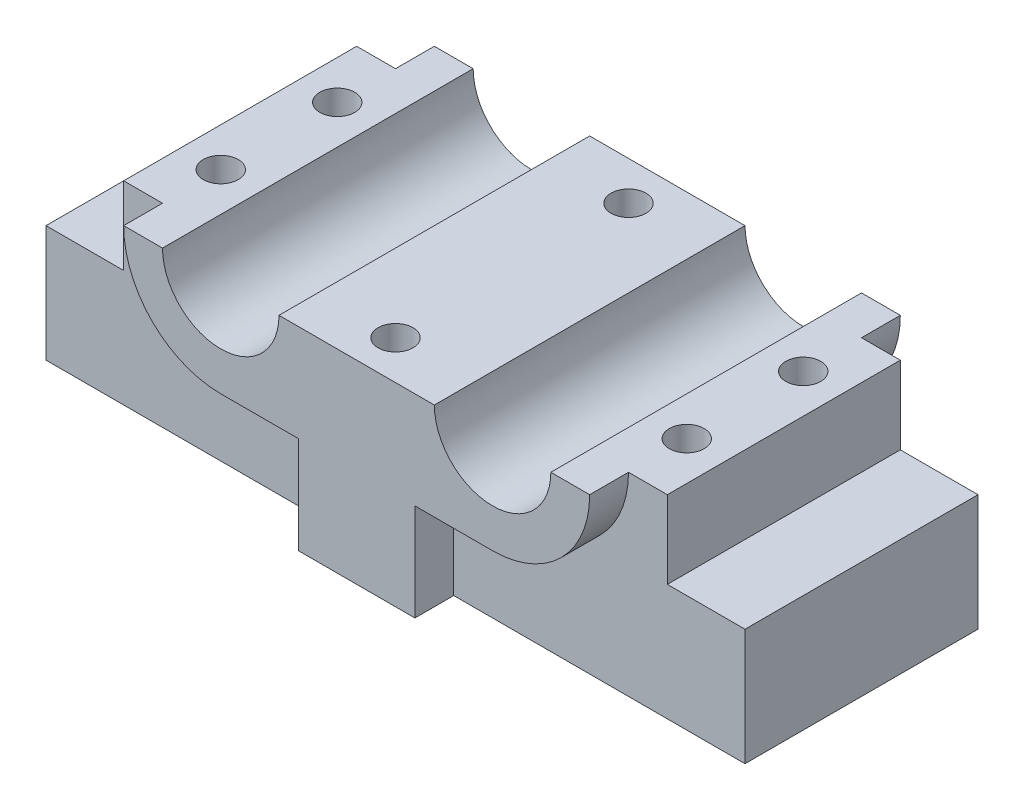
SolidWorks part; units mm, degrees
ref_plane "Front Plane" through (0, 0, 0) normal (0, 0, 1) x (1, 0, 0)
ref_plane "Top Plane" through (0, 0, 0) normal (0, 1, 0) x (1, 0, 0)
ref_plane "Right Plane" through (0, 0, 0) normal (1, 0, 0) x (0, 0, -1)
sketch "Sketch3" plane through (0, 0, 0) normal (0, 0, 1) x (1, 0, 0)
  line L1 (-45, 12.5) -> (45, 12.5)
  line L2 (-45, 12.5) -> (-45, -12.5)
  line L3 (-45, -12.5) -> (45, -12.5)
  line L4 (45, 12.5) -> (45, -12.5)
  line L5 (-45, 12.5) -> (45, -12.5) construction
  line L6 (-45, -12.5) -> (45, 12.5) construction
  point P0 (0, 0)
  dimension "D1" = 90
  dimension "D2" = 25
extrude "Boss-Extrude1" add sketch "Sketch3" along normal mid plane 40
sketch "Sketch4" plane through (0, 0, 20) normal (0, 0, 1) x (1, 0, 0)
  line L1 (-45, 12.5) -> (-35, 12.5)
  line L2 (-45, 12.5) -> (-45, 2.5)
  line L3 (-45, 2.5) -> (-35, 2.5)
  line L4 (-35, 12.5) -> (-35, 2.5)
  line L5 (45, 12.5) -> (35, 12.5)
  line L6 (45, 12.5) -> (45, 2.5)
  line L7 (45, 2.5) -> (35, 2.5)
  line L8 (35, 12.5) -> (35, 2.5)
  point P12 (54.5161, 5.0632)
  dimension "D1" = 10
  dimension "D2" = 10
  dimension "D3" = 10
extrude "Cut-Extrude1" cut sketch "Sketch4" against normal blind 40
sketch "Sketch5" plane through (0, 0, 20) normal (0, 0, 1) x (1, 0, 0)
  line L0 (17.5, 12.5) -> (30, 12.5)
  line L1 (35, 12.5) -> (-35, 12.5) construction
  line L2 (17.5, 0) -> (7.5, 0)
  line L3 (7.5, 0) -> (7.5, -12.5)
  line L4 (-45, -12.5) -> (45, -12.5) construction
  line L5 (7.5, -12.5) -> (45, -12.5)
  line L6 (45, -12.5) -> (45, 2.5)
  line L7 (45, 2.5) -> (35, 2.5)
  line L8 (35, 2.5) -> (35, 12.5)
  line L9 (35, 12.5) -> (30, 12.5)
  line L10 (0, -55) -> (0, 55) construction
  line L11 (-35, 12.5) -> (-30, 12.5)
  line L12 (-35, 2.5) -> (-35, 12.5)
  line L13 (-45, 2.5) -> (-35, 2.5)
  line L14 (-45, -12.5) -> (-45, 2.5)
  line L15 (-7.5, -12.5) -> (-45, -12.5)
  line L16 (-7.5, 0) -> (-7.5, -12.5)
  line L17 (-17.5, 0) -> (-7.5, 0)
  arc A0 (30, 12.5) -> (17.5, 0) centre (17.5, 12.5) cw
  arc A1 (-30, 12.5) -> (-17.5, 0) centre (-17.5, 12.5) ccw
  point P4 (0, 0)
  point P18 (0, 0)
  point P19 (0, 0)
  line M18 (-35, 12.5) -> (-35, 2.5)
  line M19 (-35, 2.5) -> (-45, 2.5)
  line M20 (-45, 2.5) -> (-45, -12.5)
  line M21 (-45, -12.5) -> (45, -12.5)
  line M25 (35, 12.5) -> (-35, 12.5)
  dimension "D2" = 12.5
  dimension "D1" = 17.5
  dimension "D3" = 7.5
extrude "Cut-Extrude2" cut sketch "Sketch5" against normal blind 5 contours A1 L16 L17 M25 M18 M19 M20 M21 | A0 L2 L3 L5 L6 L7 L8 L9
ref_plane "Plane1" through (0, 0, 0) normal (0, 0, -1) x (-1, 0, 0)
mirror "Mirror2" about plane through (0, 0, 0) normal (0, 0, -1) of "Cut-Extrude2"
sketch "Sketch7" plane through (0, 0, 20) normal (0, 0, 1) x (1, 0, 0)
  line L0 (-25, 12.5) -> (-10, 12.5)
  line L2 (10, 12.5) -> (25, 12.5)
  arc A0 (10, 12.5) -> (25, 12.5) centre (17.5, 12.5) ccw
  arc A1 (-25, 12.5) -> (-10, 12.5) centre (-17.5, 12.5) ccw
  dimension "D1" = 7.5
  dimension "D2" = 7.5
extrude "Cut-Extrude3" cut sketch "Sketch7" against normal through all
hole_wizard "Ø1.0mm Dowel Hole1" positions "Sketch12" profile "Sketch14" hole size "Ø1.0" standard "ISO" end condition through all
sketch "Sketch12" plane through (0, 12.5, 0) normal (0, 1, 0) x (1, 0, 0)
  point P0 (30, -7.5)
  dimension "D1" = 7.5
  dimension "D2" = 30
sketch "Sketch14" plane through (30, 12.5, 7.5) normal (1, 0, 0) x (0, 0, 1)
  line L0 (0, 0) -> (0, 25)
  line L1 (0, 25) -> (2.25, 25)
  line L2 (2.25, 25) -> (2.25, 0)
  line L5 (2.25, 0) -> (0, 0)
  line L11 (0, -6.35) -> (0, 107.95) construction
  dimension "Thru Hole Dia." = 4.5
  dimension "Thru Hole Depth" = 25
pattern_linear "LPattern1" count 2 spacing 60 along (-1, 0, 0) count 2 spacing 15 along (0, 0, -1) of "Ø1.0mm Dowel Hole1"
hole_wizard "Ø1.0mm Dowel Hole2" positions "Sketch17" profile "Sketch18" hole size "Ø1.0" standard "ISO" end condition through all
sketch "Sketch17" plane through (0, 12.5, 0) normal (0, 1, 0) x (1, 0, 0)
  point P0 (0, -15)
  dimension "D1" = 15
sketch "Sketch18" plane through (0, 12.5, 15) normal (1, 0, 0) x (0, 0, 1)
  line L0 (0, 0) -> (0, 25)
  line L1 (0, 25) -> (2.25, 25)
  line L2 (2.25, 25) -> (2.25, 0)
  line L5 (2.25, 0) -> (0, 0)
  line L11 (0, -6.35) -> (0, 107.95) construction
  dimension "Thru Hole Dia." = 4.5
  dimension "Thru Hole Depth" = 25
mirror "Mirror3" about plane through (0, 0, 0) normal (0, 0, 1) of "Ø1.0mm Dowel Hole2"
